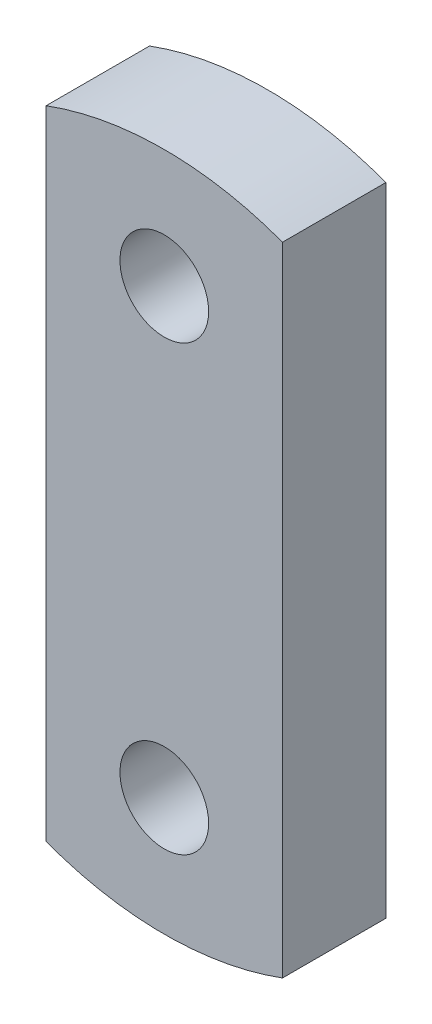
SolidWorks part; units mm, degrees
ref_plane "Front Plane" through (0, 0, 0) normal (0, 0, 1) x (1, 0, 0)
ref_plane "Top Plane" through (0, 0, 0) normal (0, 1, 0) x (1, 0, 0)
ref_plane "Right Plane" through (0, 0, 0) normal (1, 0, 0) x (0, 0, -1)
sketch "Sketch1" plane through (0, 0, 0) normal (0, 0, 1) x (1, 0, 0)
  line L0 (-40, 107.8193) -> (-40, -107.8193)
  line L1 (0, 161.071) -> (0, -182.9786) construction
  line L2 (40, 107.8193) -> (40, -107.8193)
  arc A0 (40, 107.8193) -> (-40, 107.8193) centre (0, 0) ccw
  arc A1 (-40, -107.8193) -> (40, -107.8193) centre (0, 0) ccw
  circle A2 centre (0, 75) radius 15
  circle A3 centre (0, -75) radius 15
  dimension "D1" = 230
  dimension "D3" = 30
  dimension "D4" = 30
  dimension "D2" = 40
  dimension "D5" = 75
  dimension "D6" = 75
extrude "Boss-Extrude2" add sketch "Sketch1" along normal blind 35
